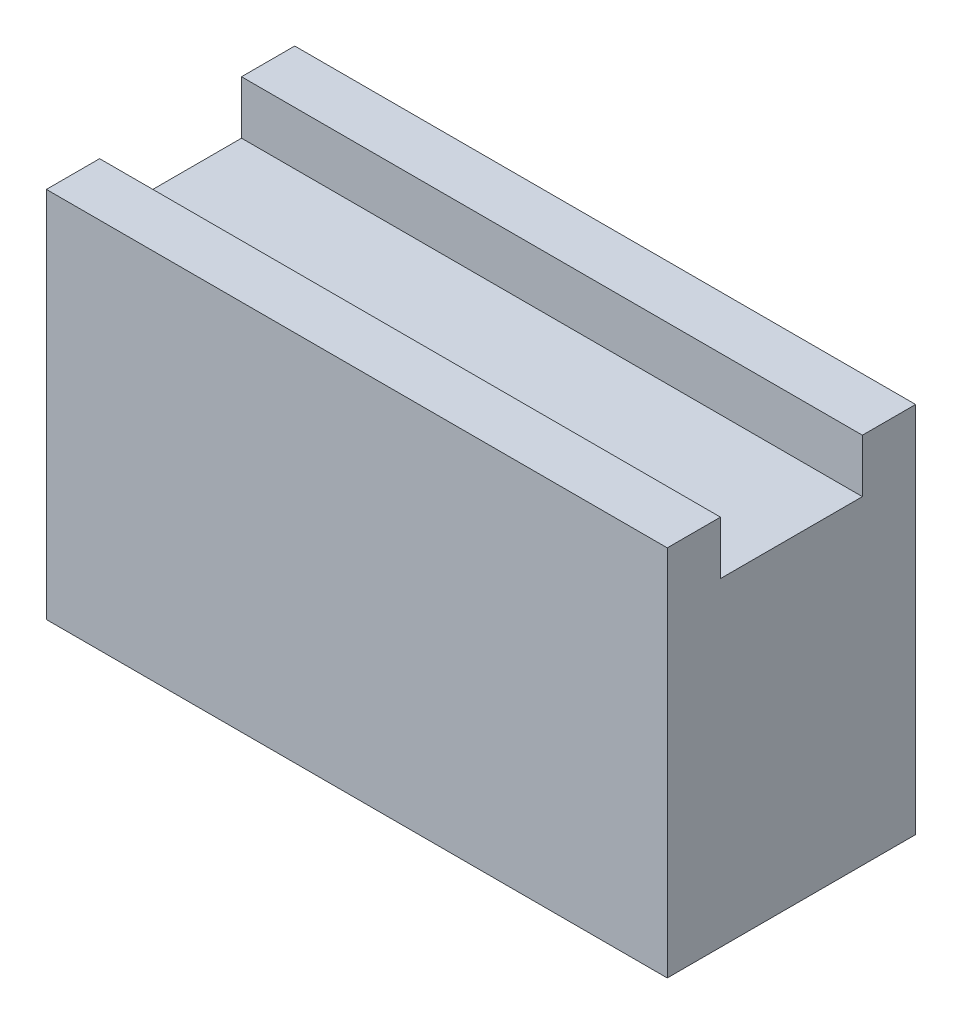
SolidWorks part; units mm, degrees
ref_plane "Front Plane" through (0, 0, 0) normal (0, 0, 1) x (1, 0, 0)
ref_plane "Top Plane" through (0, 0, 0) normal (0, 1, 0) x (1, 0, 0)
ref_plane "Right Plane" through (0, 0, 0) normal (1, 0, 0) x (0, 0, -1)
sketch "Sketch1" plane through (0, 0, 0) normal (1, 0, 0) x (0, 0, -1)
  line L0 (-7, 9) -> (-7, 12)
  line L1 (-7, -9) -> (7, -9)
  line L2 (-7, -9) -> (-7, 9)
  line L3 (-4, 9) -> (4, 9)
  line L4 (7, -9) -> (7, 9)
  line L5 (-7, -9) -> (7, 9) construction
  line L6 (-7, 9) -> (7, -9) construction
  line L7 (-7, 12) -> (-4, 12)
  line L8 (-4, 12) -> (-4, 9)
  line L9 (7, 9) -> (7, 12)
  line L10 (7, 12) -> (4, 12)
  line L11 (4, 12) -> (4, 9)
  point P0 (0, 0)
  point P12 (0, 9)
  dimension "D1" = 18
  dimension "D2" = 8
  dimension "D3" = 3
  dimension "D4" = 3
extrude "Boss-Extrude1" add sketch "Sketch1" against normal blind 35
